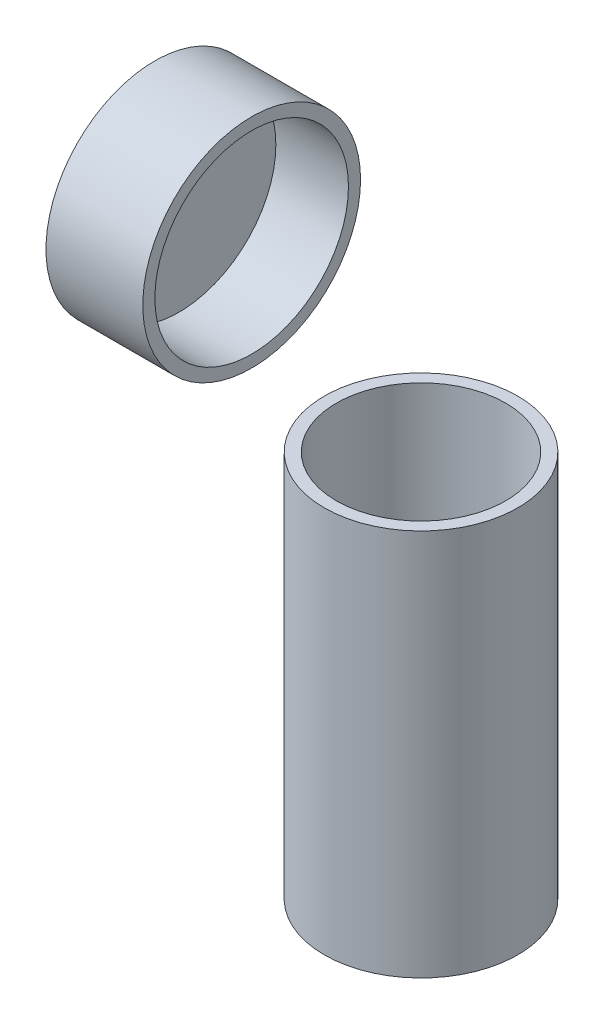
SolidWorks part; units mm, degrees
ref_plane "Front" through (0, 0, 0) normal (0, 0, 1) x (1, 0, 0)
ref_plane "Top" through (0, 0, 0) normal (0, 1, 0) x (1, 0, 0)
ref_plane "Right" through (0, 0, 0) normal (1, 0, 0) x (0, 0, -1)
sketch "Sketch1" plane through (0, 0, 0) normal (0, 1, 0) x (1, 0, 0)
  circle A0 centre (0, 0) radius 12.7
  dimension "D1" = 25.4
extrude "Boss-Extrude1" add sketch "Sketch1" along normal blind 50.8
sketch "Sketch2" plane through (0, 50.8, 0) normal (0, 1, 0) x (1, 0, 0)
  circle A0 centre (0, 0) radius 11.1125
  dimension "D1" = 22.225
extrude "Cut-Extrude1" cut sketch "Sketch2" against normal blind 44.45
ref_plane "Plane1" through (-22.225, 0, 0) normal (1, 0, 0) x (0, 0, -1)
sketch "Sketch3" plane through (-22.225, 0, 0) normal (1, 0, 0) x (0, 0, -1)
  line L0 (0, 63.5) -> (0, 0) construction
  circle A0 centre (0, 63.5) radius 14.2875
  dimension "D1" = 28.575
  dimension "D2" = 63.5
extrude "Boss-Extrude2" add sketch "Sketch3" against normal blind 12.7 separate body
sketch "Sketch4" plane through (-22.225, 0, 0) normal (1, 0, 0) x (0, 0, -1)
  circle A0 centre (0, 63.5) radius 12.7
  dimension "D1" = 25.4
extrude "Cut-Extrude2" cut sketch "Sketch4" against normal blind 9.525
